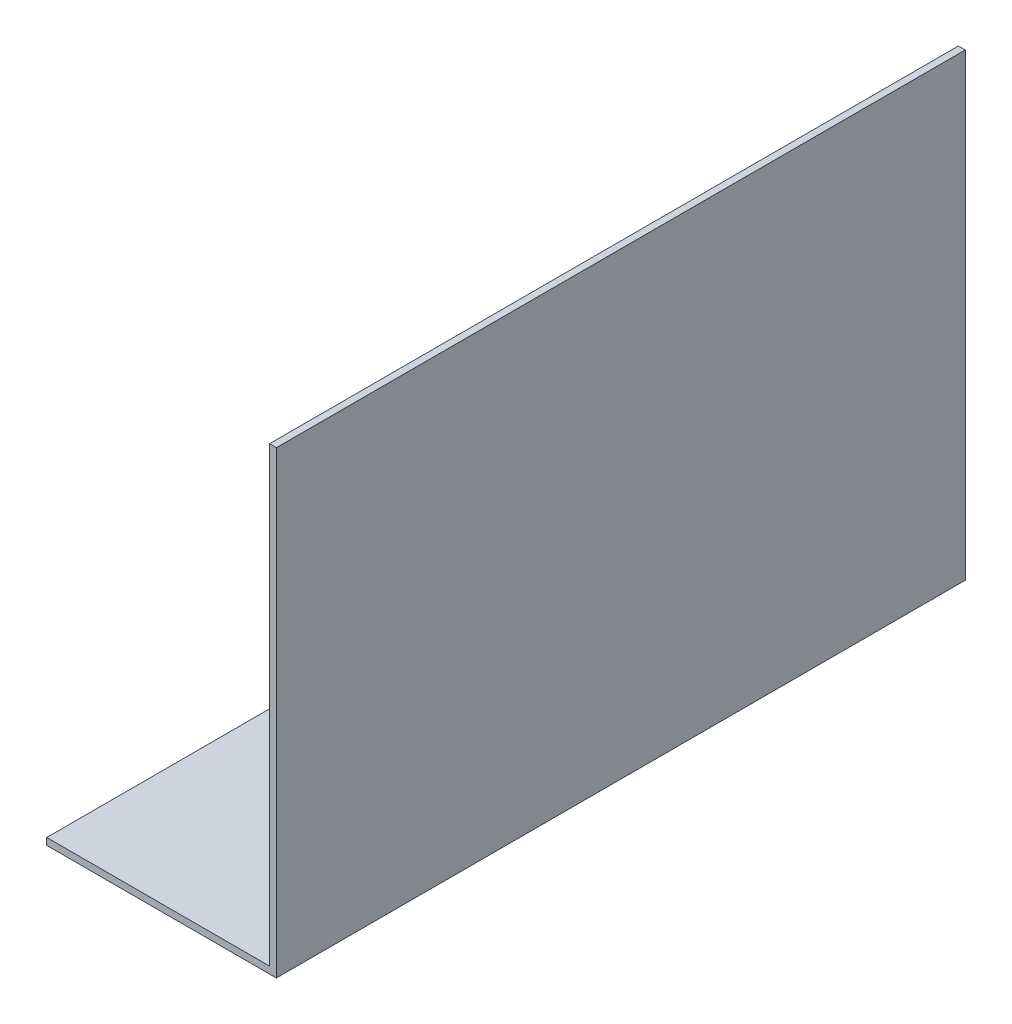
SolidWorks part; units mm, degrees
ref_plane "Plan de face" through (0, 0, 0) normal (0, 0, 1) x (1, 0, 0)
ref_plane "Plan de dessus" through (0, 0, 0) normal (0, 1, 0) x (1, 0, 0)
ref_plane "Plan de droite" through (0, 0, 0) normal (1, 0, 0) x (0, 0, -1)
sketch "Esquisse1" plane through (0, 0, 0) normal (0, 0, 1) x (1, 0, 0)
  line L0 (0, 0) -> (48.5, 0)
  line L1 (48.5, 0) -> (48.5, 98.5)
  line L2 (48.5, 98.5) -> (50, 98.5)
  line L3 (50, 98.5) -> (50, -1.5)
  line L4 (50, -1.5) -> (0, -1.5)
  line L5 (0, -1.5) -> (0, 0)
  dimension "D1" = 1.5
  dimension "D2" = 1.5
  dimension "D3" = 100
  dimension "D4" = 50
extrude "Boss.-Extru.1" add sketch "Esquisse1" along normal blind 150
